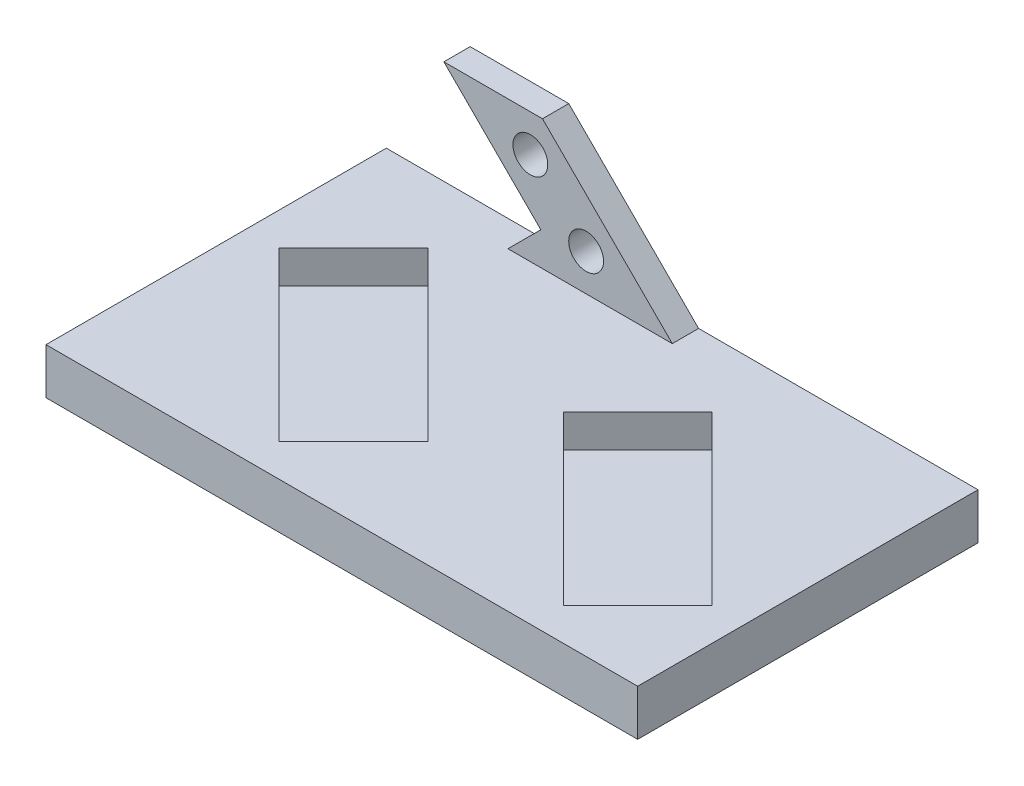
SolidWorks part; units mm, degrees
ref_plane "Front Plane" through (0, 0, 0) normal (0, 0, 1) x (1, 0, 0)
ref_plane "Top Plane" through (0, 0, 0) normal (0, 1, 0) x (1, 0, 0)
ref_plane "Right Plane" through (0, 0, 0) normal (1, 0, 0) x (0, 0, -1)
sketch "Sketch1" plane through (0, 0, 0) normal (0, 1, 0) x (1, 0, 0)
  line L7 (5, -21.3137) -> (30.4558, -46.7696)
  line L8 (0, 0) -> (90, 0)
  line L9 (0, 0) -> (0, -51.7696)
  line L10 (0, -51.7696) -> (90, -51.7696)
  line L11 (90, 0) -> (90, -51.7696)
  line L12 (30.4558, -46.7696) -> (41.7696, -35.4558)
  line L13 (41.7696, -35.4558) -> (16.3137, -10)
  line L14 (16.3137, -10) -> (5, -21.3137)
  line L15 (29.0416, -22.7279) -> (17.7279, -34.0416) construction
  line L16 (10.6569, -15.6569) -> (36.1127, -41.1127) construction
  line L17 (45, 0) -> (45, -51.7696) construction
  line L18 (48.2304, -21.3137) -> (73.6863, -46.7696)
  line L19 (73.6863, -46.7696) -> (85, -35.4558)
  line L20 (85, -35.4558) -> (59.5442, -10)
  line L21 (59.5442, -10) -> (48.2304, -21.3137)
  line L22 (72.2721, -22.7279) -> (60.9584, -34.0416) construction
  dimension "D2" = 45
  dimension "D3" = 10
  dimension "D4" = 16
  dimension "D5" = 36
  dimension "D7" = 5
  dimension "D8" = 5
  dimension "D10" = 16
  dimension "D11" = 36
  dimension "D12" = 5
  dimension "D13" = 5
extrude "Boss-Extrude1" add sketch "Sketch1" along normal blind 5
sketch "Sketch5" plane through (0, 0, 0) normal (0, 0, -1) x (-1, 0, 0)
  line L0 (-52.5, 0) -> (-27.7513, 24.7487)
  line L1 (0, 0) -> (-90, 0) construction
  line L2 (-27.7513, 24.7487) -> (-12.7513, 24.7487)
  line L3 (-12.7513, 24.7487) -> (-37.5, 0)
  line L4 (-37.5, 0) -> (-52.5, 0)
  line L5 (-20.2513, 24.7487) -> (-45, 0) construction
  line L6 (-45, 0) -> (-45, 5) construction
  line L7 (0, 5) -> (-90, 5) construction
  circle A0 centre (-25.9081, 19.0919) radius 2.65
  circle A1 centre (-34.3934, 10.6066) radius 2.65
  dimension "D3" = 5.3
  dimension "D1" = 45
  dimension "D2" = 12
  dimension "D4" = 15
  dimension "D5" = 35
  dimension "D6" = 8
extrude "Boss-Extrude2" add sketch "Sketch5" against normal blind 4
chamfer "Chamfer1" distance 10 angle 45 1 edges at (32.5, 5, 2)
sketch "Sketch6" plane through (0, 0, 0) normal (0, -1, 0) x (1, 0, 0)
  line L1 (0, 51.7696) -> (90, 51.7696)
  line L2 (0, 51.7696) -> (0, 0)
  line L3 (0, 0) -> (90, 0)
  line L4 (90, 51.7696) -> (90, 0)
extrude "Boss-Extrude3" add sketch "Sketch6" along normal blind 2
